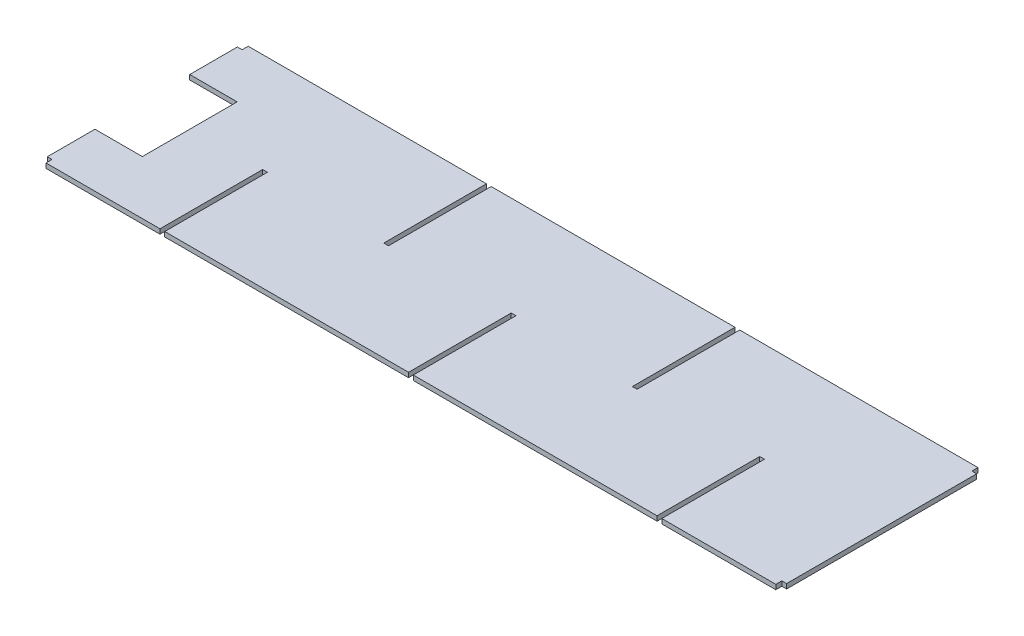
SolidWorks part; units mm, degrees
ref_plane "Front Plane" through (0, 0, 0) normal (0, 0, 1) x (1, 0, 0)
ref_plane "Top Plane" through (0, 0, 0) normal (0, 1, 0) x (1, 0, 0)
ref_plane "Right Plane" through (0, 0, 0) normal (1, 0, 0) x (0, 0, -1)
sketch "Sketch1" plane through (0, 0, 0) normal (0, 1, 0) x (1, 0, 0)
  line L1 (0, 0) -> (234, 0)
  line L2 (0, 0) -> (0, 64)
  line L3 (0, 64) -> (234, 64)
  line L4 (234, 0) -> (234, 64)
  dimension "D1" = 234
  dimension "D2" = 64
extrude "Boss-Extrude1" add sketch "Sketch1" along normal blind 1.5
sketch "Sketch2" plane through (0, 1.5, 0) normal (0, 1, 0) x (1, 0, 0)
  line L0 (0, 0) -> (234, 0) construction
  line L1 (37.5833, 0) -> (39.0833, 0)
  line L2 (37.5833, 0) -> (37.5833, 32.5)
  line L3 (37.5833, 32.5) -> (39.0833, 32.5)
  line L4 (39.0833, 0) -> (39.0833, 32.5)
  line L5 (234, 64) -> (0, 64) construction
  line L6 (76.9167, 64) -> (78.4167, 64)
  line L7 (76.9167, 64) -> (76.9167, 31.5)
  line L8 (76.9167, 31.5) -> (78.4167, 31.5)
  line L9 (78.4167, 64) -> (78.4167, 31.5)
  line L10 (116.25, 0) -> (116.25, 32.5)
  line L11 (116.25, 0) -> (117.75, 0)
  line L12 (117.75, 0) -> (117.75, 32.5)
  line L13 (116.25, 32.5) -> (117.75, 32.5)
  line L14 (194.9167, 0) -> (194.9167, 32.5)
  line L15 (194.9167, 0) -> (196.4167, 0)
  line L16 (196.4167, 0) -> (196.4167, 32.5)
  line L17 (194.9167, 32.5) -> (196.4167, 32.5)
  line L18 (155.5833, 64) -> (155.5833, 31.5)
  line L19 (155.5833, 64) -> (157.0833, 64)
  line L20 (157.0833, 64) -> (157.0833, 31.5)
  line L21 (155.5833, 31.5) -> (157.0833, 31.5)
  line L22 (0, 64) -> (0, 0) construction
  line L23 (0, 32) -> (37.5833, 32) construction
  line L24 (0, 0) -> (1.5, 0)
  line L25 (0, 0) -> (0, 1.915)
  line L26 (0, 1.915) -> (1.5, 1.915)
  line L27 (1.5, 0) -> (1.5, 1.915)
  line L28 (0, 64) -> (1.5, 64)
  line L29 (0, 64) -> (0, 62.085)
  line L30 (0, 62.085) -> (1.5, 62.085)
  line L31 (1.5, 64) -> (1.5, 62.085)
  line L32 (234, 64) -> (232.5, 64)
  line L33 (234, 64) -> (234, 62.085)
  line L34 (234, 62.085) -> (232.5, 62.085)
  line L35 (232.5, 64) -> (232.5, 62.085)
  line L36 (234, 0) -> (232.5, 0)
  line L37 (234, 0) -> (234, 1.915)
  line L38 (234, 1.915) -> (232.5, 1.915)
  line L39 (232.5, 0) -> (232.5, 1.915)
  line L40 (234, 32) -> (196.4167, 32) construction
  line L41 (234, 0) -> (234, 64) construction
  line L43 (0, 47) -> (15, 47)
  line L44 (0, 47) -> (0, 17)
  line L45 (0, 17) -> (15, 17)
  line L46 (15, 47) -> (15, 17)
  point P56 (0, 32)
  dimension "D1" = 1.5
  dimension "D2" = 39.3333
  dimension "D4" = 2
  dimension "D5" = 15
  dimension "D6" = 32.5
  dimension "D7" = 78.6667
  dimension "D8" = 78.6667
  dimension "D9" = 60.17
  dimension "D10" = 1.5
  dimension "D11" = 32.5
  dimension "D12" = 30
  dimension "D3" = 3
extrude "Cut-Extrude1" cut sketch "Sketch2" against normal through all both and the other way through all
